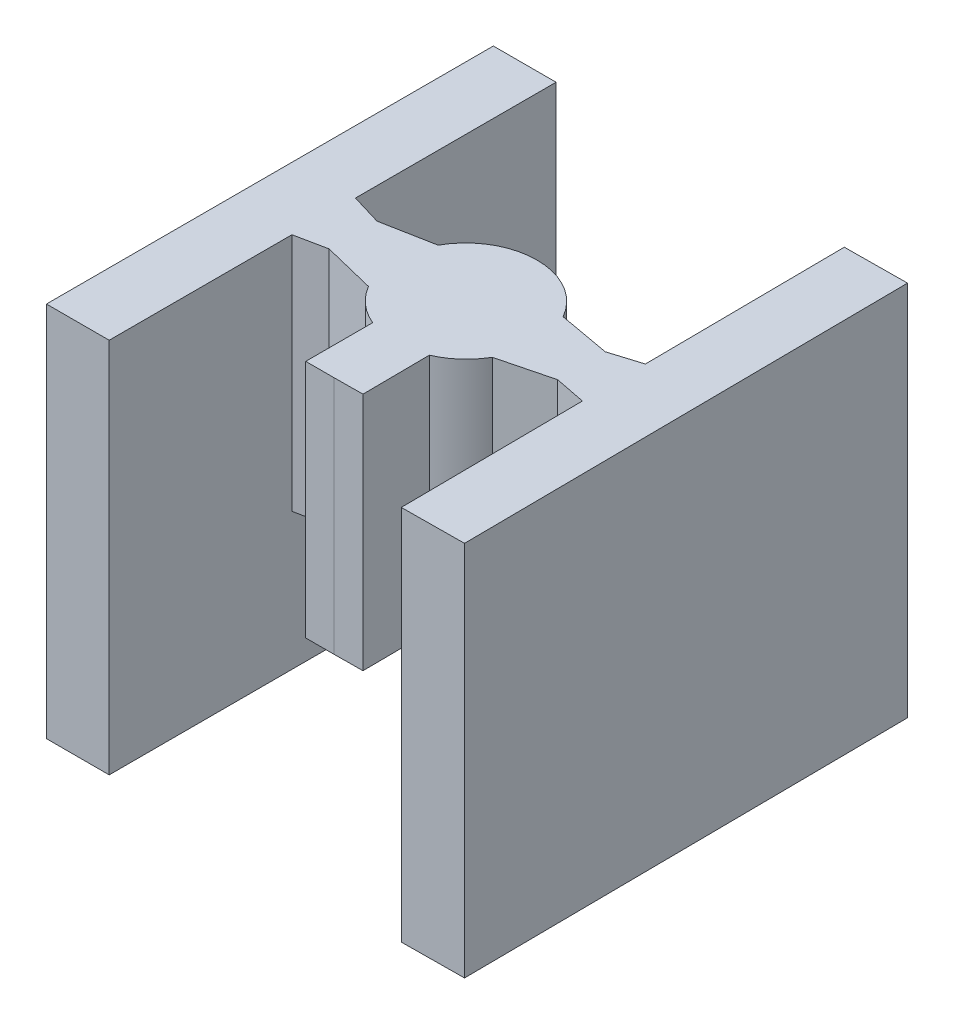
SolidWorks part; units mm, degrees
ref_plane "Front Plane" through (0, 0, 0) normal (0, 0, 1) x (1, 0, 0)
ref_plane "Top Plane" through (0, 0, 0) normal (0, 1, 0) x (1, 0, 0)
ref_plane "Right Plane" through (0, 0, 0) normal (1, 0, 0) x (0, 0, -1)
sketch "Sketch1" plane through (0, 0, 0) normal (0, 1, 0) x (1, 0, 0)
  line L0 (118.5, 375) -> (592.5, 375) construction
  line L1 (27.997, 26.1044) -> (30.497, 26.1044)
  line L2 (32.9969, 26.126) -> (30.497, 26.1044)
  line L3 (32.9969, 26.126) -> (32.9463, 31.9923)
  line L4 (43.0882, 40.7909) -> (40.3953, 39.9592)
  line L5 (42.9365, 58.3777) -> (43.0882, 40.7909)
  line L6 (48.4363, 58.4251) -> (42.9365, 58.3777)
  line L7 (48.7742, 19.251) -> (48.4363, 58.4251)
  line L8 (43.2744, 19.2036) -> (48.7742, 19.251)
  line L9 (43.1362, 35.2238) -> (43.2744, 19.2036)
  line L10 (40.4315, 35.7538) -> (43.1362, 35.2238)
  line L11 (24.9791, 40.7283) -> (20.4796, 39.8733)
  line L12 (25.0572, 34.5446) -> (20.4796, 35.6677)
  line L13 (20.4796, 35.6677) -> (17.7796, 35.1144)
  line L14 (17.7796, 35.1144) -> (17.7796, 19.0937)
  line L15 (17.7796, 19.0937) -> (12.2796, 19.0937)
  line L16 (12.2796, 19.0937) -> (12.2796, 58.2692)
  line L17 (12.2796, 58.2692) -> (17.7796, 58.2692)
  line L18 (17.7796, 58.2692) -> (17.7796, 40.6817)
  line L19 (17.7796, 40.6817) -> (20.4796, 39.8733)
  line L20 (35.8639, 34.5912) -> (40.4315, 35.7538)
  line L21 (27.997, 26.1044) -> (27.997, 31.971)
  line L22 (35.8886, 40.7754) -> (40.3953, 39.9592)
  arc A0 (25.0572, 34.5446) -> (27.997, 31.971) centre (30.4202, 37.7047) ccw
  arc A1 (30.4202, 43.9295) -> (24.9791, 40.7283) centre (30.4202, 37.7047) ccw
  arc A2 (30.4202, 43.9295) -> (35.8886, 40.7754) centre (30.4738, 37.7049) cw
  arc A3 (35.8639, 34.5912) -> (32.9463, 31.9923) centre (30.4738, 37.7049) cw
  dimension "D9" = 30.4202
  dimension "D2" = 6.2248
  dimension "D1" = 39.1755
  dimension "D3" = 12.2796
  dimension "D4" = 5.5
  dimension "D5" = 7.2775
  dimension "D6" = 19.0937
  dimension "D7" = 27.997
  dimension "D8" = 7.1994
  dimension "D10" = 30.497
  dimension "D11" = 4.2056
  dimension "D12" = 17.5875
  dimension "D13" = 16.0208
  dimension "D14" = 26.1044
  dimension "D15" = 31.971
  dimension "D16" = 30.4738
  dimension "D17" = 35.8639
  dimension "D18" = 2.7
  dimension "D19" = 2.7
  dimension "D20" = 35.8886
  dimension "D21" = 40.3953
  dimension "D22" = 40.4315
extrude "Boss-Extrude1" add sketch "Sketch1" along normal blind 33
sketch "Sketch2" plane through (0, 0, 0) normal (0, -1, 0) x (1, 0, 0)
  line L0 (17.7796, -35.1144) -> (17.7796, -40.6817)
  line L1 (17.7796, -40.6817) -> (20.4796, -39.8733)
  line L2 (20.4796, -39.8733) -> (24.9791, -40.7283)
  line L4 (25.0572, -34.5446) -> (20.4796, -35.6677)
  line L5 (27.997, -31.971) -> (27.997, -26.1044)
  line L6 (27.997, -26.1044) -> (32.9969, -26.126)
  line L7 (32.9969, -26.126) -> (32.9463, -31.9923)
  line L8 (35.8639, -34.5912) -> (40.4315, -35.7538)
  line L9 (40.4315, -35.7538) -> (43.1362, -35.2238)
  line L10 (43.1362, -35.2238) -> (43.0882, -40.7909)
  line L11 (43.0882, -40.7909) -> (40.3953, -39.9592)
  line L12 (40.3953, -39.9592) -> (35.8886, -40.7754)
  arc A0 (25.0572, -34.5446) -> (27.997, -31.971) centre (30.4202, -37.7047) cw
  arc A1 (32.9463, -31.9923) -> (35.8639, -34.5912) centre (30.4738, -37.7049) cw
  arc A2 (24.9791, -40.7283) -> (30.4202, -43.9295) centre (30.4202, -37.7047) ccw
  arc A3 (30.4202, -43.9295) -> (35.8886, -40.7754) centre (30.4202, -37.6119) ccw
extrude "Cut-Extrude1" cut sketch "Sketch2" against normal blind 12 and the other way through all
sketch "Sketch3" plane through (0, 0, -26.1044) normal (0, 0, 1) x (1, 0, 0)
  line L0 (30.497, 33) -> (30.497, 0) construction
  line L1 (27.997, 12) -> (37.4782, 12)
  line L2 (27.997, 12) -> (27.997, -5.0217)
  line L3 (27.997, -5.0217) -> (37.4782, -5.0217)
  line L4 (37.4782, 12) -> (37.4782, -5.0217)
  line L5 (27.997, 33) -> (30.497, 33) construction
  dimension "D1" = 6.9812
  dimension "D2" = 38.0217
extrude "Cut-Extrude2" cut sketch "Sketch3" against normal blind 22
